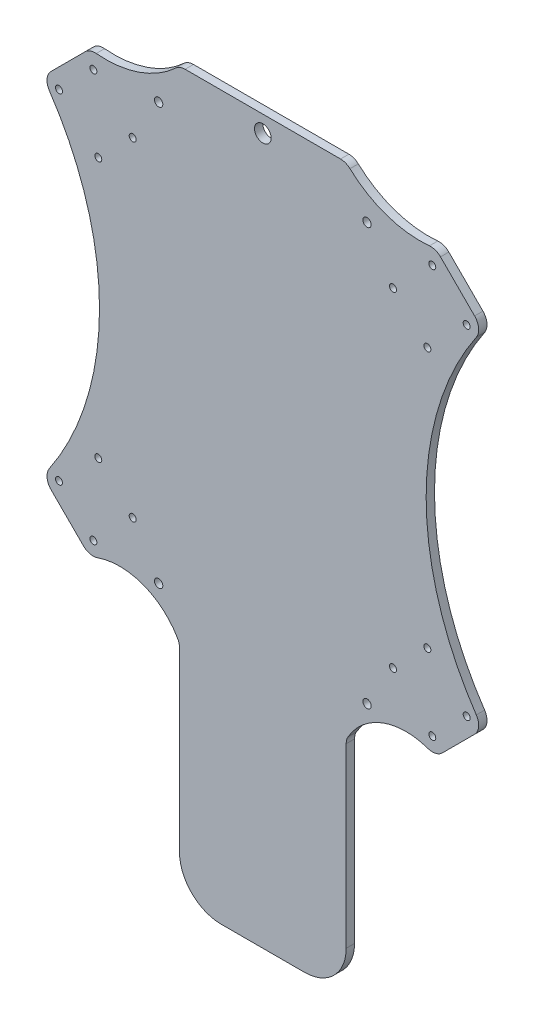
SolidWorks part; units mm, degrees
material "Hexcel AS4C (3000 Filaments)"
ref_plane "Front Plane" through (0, 0, 0) normal (0, 0, 1) x (1, 0, 0)
ref_plane "Top Plane" through (0, 0, 0) normal (0, 1, 0) x (1, 0, 0)
ref_plane "Right Plane" through (0, 0, 0) normal (1, 0, 0) x (0, 0, -1)
sketch "Sketch2" plane through (0, 0, 0) normal (0, 0, 1) x (1, 0, 0)
  line L0 (0, 0) -> (0, 50000) construction
  line L1 (0, 0) -> (35355.3391, 35355.3391) construction
  line L2 (0, 0) -> (35355.3391, -35355.3391) construction
  line L3 (-79.196, 62.2254) -> (-62.2254, 79.196)
  line L4 (0, 0) -> (-50000, 0) construction
  line L5 (-79.196, -62.2254) -> (-62.2254, -79.196)
  line L6 (30, 90) -> (-30, 90)
  line L7 (30, -90) -> (30, -155)
  line L8 (79.196, -62.2254) -> (62.2254, -79.196)
  line L9 (-30, -90) -> (-30, -155)
  line L10 (-15, -170) -> (15, -170)
  line L11 (79.196, 62.2254) -> (62.2254, 79.196)
  line L12 (-30, -90) -> (30, -170) construction
  line L13 (-30, -170) -> (30, -90) construction
  arc A0 (-79.196, 62.2254) -> (-79.196, -62.2254) centre (-163.8225, 0) cw
  arc A1 (-62.2254, 79.196) -> (-30, 90) centre (-56.6326, 115.976) ccw
  arc A2 (-62.2254, -79.196) -> (-30, -90) centre (-51.5147, -100.7107) cw
  arc A3 (15, -170) -> (30, -155) centre (15, -155) ccw
  arc A4 (-15, -170) -> (-30, -155) centre (-15, -155) cw
  arc A5 (62.2254, -79.196) -> (30, -90) centre (51.5147, -100.7107) ccw
  arc A6 (79.196, 62.2254) -> (79.196, -62.2254) centre (163.8225, 0) ccw
  arc A7 (62.2254, 79.196) -> (30, 90) centre (56.6326, 115.976) cw
  circle A8 centre (-37.5, 75) radius 1.5
  circle A9 centre (37.5, 75) radius 1.5
  circle A10 centre (37.5, -75) radius 1.5
  circle A11 centre (-37.5, -75) radius 1.5
  circle A12 centre (0, 84) radius 3
  point P16 (-70.7107, 70.7107)
  point P24 (0, -130)
  point P32 (0, -170)
  point P45 (0, 90)
  dimension "D4" = 75
  dimension "D8" = 6
  dimension "D1" = 170
  dimension "D2" = 45
  dimension "D3" = 45
  dimension "D5" = 30
  dimension "D6" = 60
  dimension "D7" = 37.5
extrude "Boss-Extrude1" add sketch "Sketch2" along normal blind 3
sketch "Sketch3" plane through (0, 0, 3) normal (0, 0, 1) x (1, 0, 0)
  line L0 (-70.7107, 70.7107) -> (35284.6284, -35284.6284) construction
  line L1 (-79.196, 62.2254) -> (-62.2254, 79.196) construction
  line L2 (0, 90) -> (0, 50090) construction
  line L3 (30, 90) -> (-30, 90) construction
  line L4 (70.7107, 70.7107) -> (35426.0497, 35426.0497) construction
  line L5 (79.196, 62.2254) -> (62.2254, 79.196) construction
  line L6 (0, 0) -> (50000, 0) construction
  circle A0 centre (-73.3623, 60.988) radius 1.25
  circle A1 centre (-59.2202, 46.8458) radius 1.25
  circle A2 centre (-60.988, 73.3623) radius 1.25
  circle A3 centre (-46.8458, 59.2202) radius 1.25
  circle A4 centre (59.2202, 46.8458) radius 1.25
  circle A5 centre (73.3623, 60.988) radius 1.25
  circle A6 centre (60.988, 73.3623) radius 1.25
  circle A7 centre (46.8458, 59.2202) radius 1.25
  circle A8 centre (-59.2202, -46.8458) radius 1.25
  circle A9 centre (-46.8458, -59.2202) radius 1.25
  circle A10 centre (-60.988, -73.3623) radius 1.25
  circle A11 centre (-73.3623, -60.988) radius 1.25
  circle A12 centre (59.2202, -46.8458) radius 1.25
  circle A13 centre (73.3623, -60.988) radius 1.25
  circle A14 centre (60.988, -73.3623) radius 1.25
  circle A15 centre (46.8458, -59.2202) radius 1.25
  point P6 (-70.7107, 70.7107)
  point P17 (0, 90)
  point P30 (70.7107, 70.7107)
  dimension "D1" = 8.75
  dimension "D3" = 8.75
  dimension "D2" = 5
  dimension "D4" = 20
extrude "45 Degrees" cut sketch "Sketch3" against normal through all
fillet "Fillet1" radius 5 1 edges at (-30, 90, 1.5)
fillet "Fillet2" radius 5 1 edges at (-79.196, 62.2254, 1.5)
fillet "Fillet3" radius 5 1 edges at (-62.2254, 79.196, 1.5)
fillet "Fillet4" radius 5 1 edges at (62.2254, 79.196, 1.5)
fillet "Fillet5" radius 5 1 edges at (30, 90, 1.5)
fillet "Fillet6" radius 5 1 edges at (79.196, 62.2254, 1.5)
fillet "Fillet7" radius 5 1 edges at (79.196, -62.2254, 1.5)
fillet "Fillet8" radius 5 1 edges at (62.2254, -79.196, 1.5)
fillet "Fillet10" radius 5 1 edges at (30, -90, 1.5)
fillet "Fillet11" radius 5 1 edges at (-30, -90, 1.5)
fillet "Fillet12" radius 5 1 edges at (-79.196, -62.2254, 1.5)
fillet "Fillet13" radius 5 1 edges at (-62.2254, -79.196, 1.5)
sketch "Sketch4" plane through (0, 0, 3) normal (0, 0, 1) x (1, 0, 0)
  line L0 (-60.988, 71.5946) -> (-60.988, -49928.4054) construction
  line L1 (-62.7557, 73.3623) -> (49937.2443, 73.3623) construction
  line L2 (-62.4001, 71.3456) -> (-28741.2219, -40886.2567) construction
  line L3 (-66.3406, 66.4749) -> (40891.2616, -28612.347) construction
  line L4 (0, 0) -> (0, 50000) construction
  line L5 (0, 0) -> (50000, 0) construction
  circle A1 centre (-69.5698, 61.1062) radius 1.25
  circle A2 centre (-60.988, 73.3623) radius 1.25
  circle A3 centre (60.988, 73.3623) radius 1.25
  circle A4 centre (-46.1417, 59.9613) radius 1.25
  circle A5 centre (-53.1868, 49.6346) radius 1.25
  circle A6 centre (46.1417, 59.9613) radius 1.25
  circle A7 centre (53.1868, 49.6346) radius 1.25
  circle A8 centre (69.5698, 61.1062) radius 1.25
  circle A9 centre (60.988, -73.3623) radius 1.25
  circle A10 centre (69.5698, -61.1062) radius 1.25
  circle A11 centre (46.1417, -59.9613) radius 1.25
  circle A12 centre (53.1868, -49.6346) radius 1.25
  circle A13 centre (-60.988, -73.3623) radius 1.25
  circle A14 centre (-53.1868, -49.6346) radius 1.25
  circle A15 centre (-46.1417, -59.9613) radius 1.25
  circle A16 centre (-69.5698, -61.1062) radius 1.25
  dimension "D3" = 20
  dimension "D2" = 6.25
  dimension "D4" = 6.25
  dimension "D5" = 6.25
  dimension "D6" = 20
extrude "35 Degress" [suppressed] cut sketch "Sketch4" against normal through all
